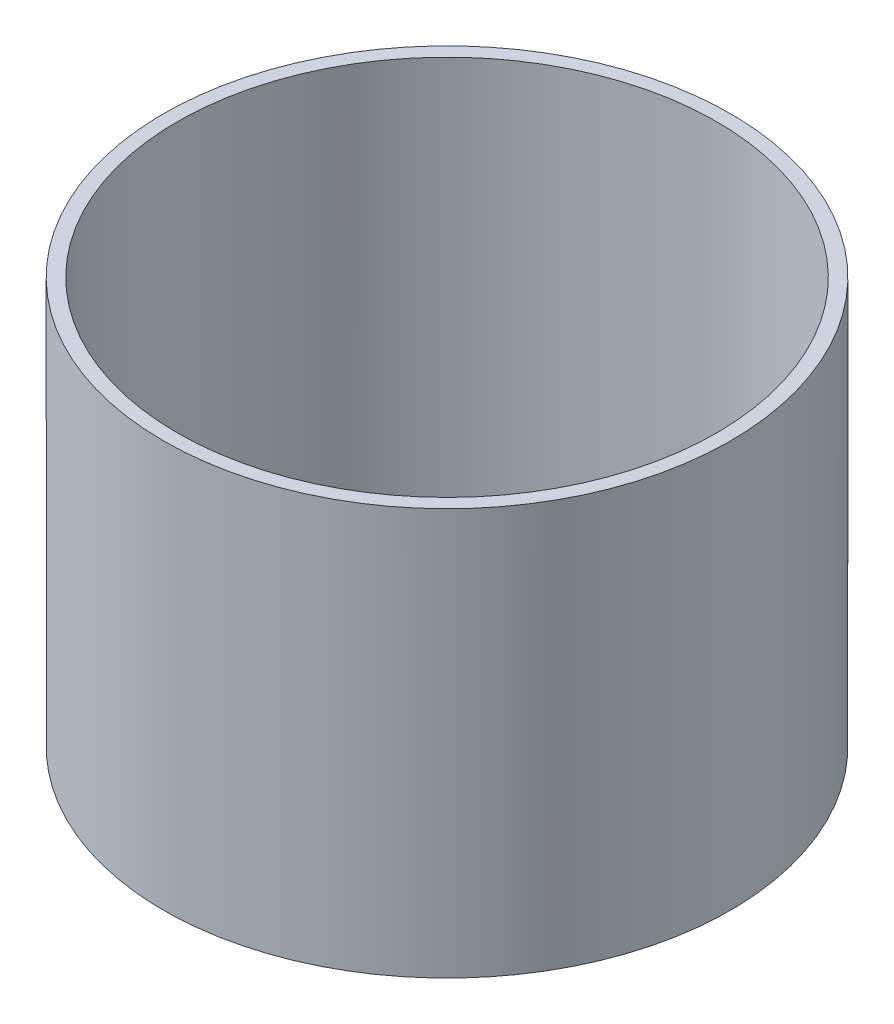
SolidWorks part; units mm, degrees
ref_plane "Front Plane" through (0, 0, 0) normal (0, 0, 1) x (1, 0, 0)
ref_plane "Top Plane" through (0, 0, 0) normal (0, 1, 0) x (1, 0, 0)
ref_plane "Right Plane" through (0, 0, 0) normal (1, 0, 0) x (0, 0, -1)
sketch "Sketch1" plane through (0, 0, 0) normal (0, 1, 0) x (1, 0, 0)
  circle A0 centre (0, 0) radius 41
  circle A1 centre (0, 0) radius 39
  dimension "D1" = 82
  dimension "D2" = 2
extrude "Boss-Extrude1" add sketch "Sketch1" along normal blind 58.8
sketch "Sketch2" plane through (0, 0, 0) normal (0, 0, 1) x (1, 0, 0)
  circle A1 centre (0, 0) radius 10.45
  dimension "D2" = 20.9
extrude "Cut-Extrude1" cut sketch "Sketch2" against normal through all
